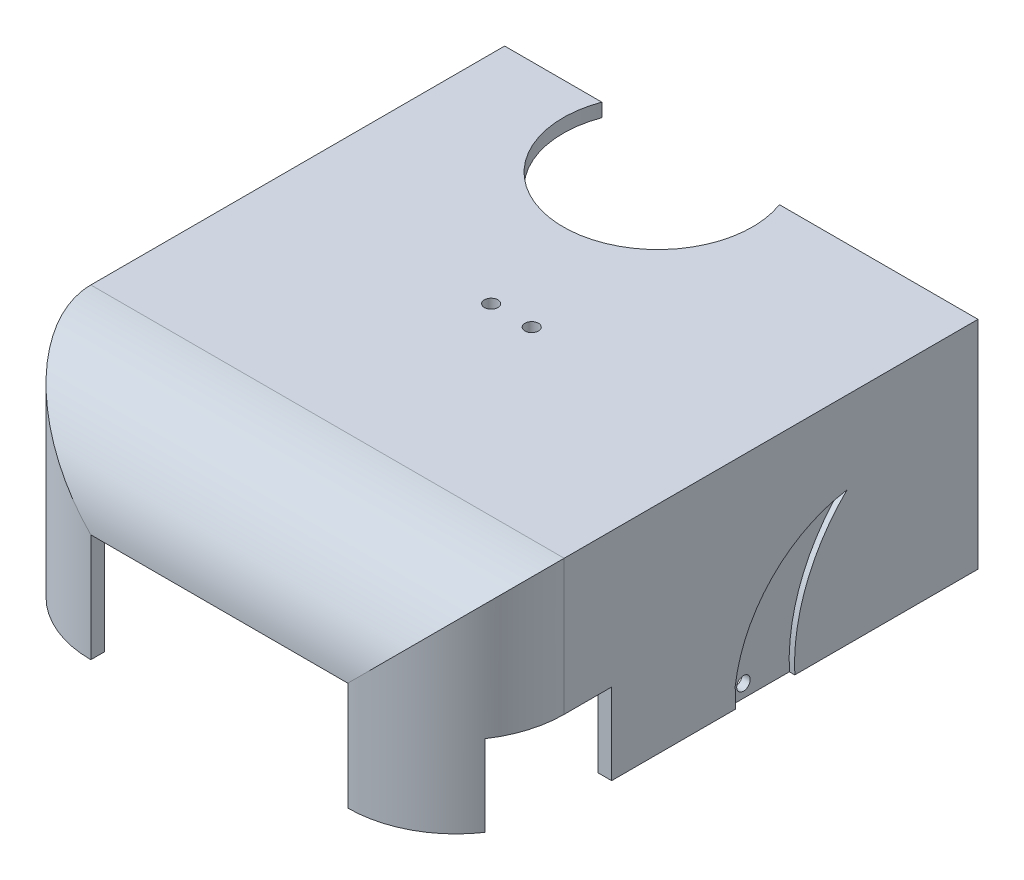
SolidWorks part; units mm, degrees
ref_plane "前基準面" through (0, 0, 0) normal (0, 0, 1) x (1, 0, 0)
ref_plane "上基準面" through (0, 0, 0) normal (0, 1, 0) x (1, 0, 0)
ref_plane "右基準面" through (0, 0, 0) normal (1, 0, 0) x (0, 0, -1)
sketch "草圖1" plane through (0, 0, 0) normal (0, 0, 1) x (1, 0, 0)
  line L1 (-87.5, -80) -> (87.5, -80)
  line L2 (-87.5, -80) -> (-87.5, 80)
  line L3 (-87.5, 80) -> (87.5, 80)
  line L4 (87.5, -80) -> (87.5, 80)
  line L5 (-87.5, -80) -> (87.5, 80) construction
  line L6 (-87.5, 80) -> (87.5, -80) construction
  point P0 (0, 0)
  dimension "D1" = 175
  dimension "D2" = 160
extrude "填料-伸長1" add sketch "草圖1" along normal blind 193
sketch "草圖4" plane through (0, 0, 0) normal (0, 1, 0) x (1, 0, 0)
  line L0 (0, 0) -> (0, -200)
  line L1 (0, -200) -> (-165, -200)
  line L2 (-165, -200) -> (-165, 0)
  line L3 (0, -200) -> (110, -200)
  line L4 (110, -200) -> (110, 0)
  line L5 (110, 0) -> (-165, 0)
  dimension "D1" = 165
  dimension "D2" = 200
sketch "草圖5" plane through (0, 0, 0) normal (1, 0, 0) x (0, 0, -1)
  line L0 (-200, 0) -> (-200, 160)
  line L1 (0, 0) -> (-200, 0) construction
  line L2 (-200, 160) -> (0, 160)
  dimension "D1" = 160
fillet "圓角8" radius 40 4 edges at (87.5, 0, 193) (0, 80, 193) (-87.5, 0, 193) (0, -80, 193)
shell "薄殼2" thickness 5
ref_plane "平面1" through (85, 0, 0) normal (1, 0, 0) x (0, 0, -1)
ref_plane "平面2" through (0, 80, 0) normal (0, 1, 0) x (1, 0, 0)
sketch "草圖8" plane through (0, 80, 0) normal (0, 1, 0) x (1, 0, 0)
  line L1 (87.5, 0) -> (-87.5, 0) construction
  line L3 (-87.5, 0) -> (17, 0)
  line L4 (-87.5, 0) -> (-87.5, -197.279)
  line L5 (-87.5, -197.279) -> (17, -197.279)
  line L6 (17, 0) -> (17, -197.279)
sketch "草圖9" plane through (0, 0, 193) normal (0, 0, 1) x (1, 0, 0)
  line L1 (-47.5, 40) -> (47.5, 40)
  line L2 (-47.5, 40) -> (-47.5, -40)
  line L3 (-47.5, -40) -> (47.5, -40)
  line L4 (47.5, 40) -> (47.5, -40)
extrude "除料-伸長3" cut sketch "草圖9" against normal blind 10
sketch "草圖10" plane through (0, 80, 0) normal (0, 1, 0) x (1, 0, 0)
  line L0 (0, 0) -> (-87.5, 0) construction
  line L1 (87.5, 0) -> (-87.5, 0) construction
  line L2 (-87.5, 0) -> (-43.75, 0) construction
  line L3 (-43.75, 0) -> (-87.5, 0) construction
  line L4 (-87.5, 0) -> (-65.625, 0) construction
  line L5 (-65.625, 0) -> (-43.75, -12.1031) construction
  line L6 (-43.75, 0) -> (-43.75, -31.8331) construction
  line L7 (-43.75, -12.1031) -> (-18.75, -12.1031)
  circle A0 centre (-18.75, -12.1031) radius 35
  dimension "D1" = 25
  dimension "D2" = 25
extrude "除料-伸長4" cut sketch "草圖10" against normal blind 160 contours A0
ref_plane "平面3" through (90, 0, 0) normal (1, 0, 0) x (0, 0, -1)
sketch "草圖12" plane through (90, 0, 0) normal (1, 0, 0) x (0, 0, -1)
  line L1 (-175.4577, -30) -> (-135.4577, 30) construction
  line L3 (-135.4577, -30) -> (-135.4577, 30)
  line L7 (-135.4577, 30) -> (-175.4577, 30)
  line L8 (-175.4577, 30) -> (-175.4577, -30)
  line L9 (-175.4577, -30) -> (-135.4577, -30)
  line L10 (0, 0) -> (-208.2911, 0) construction
  line L11 (-175.4577, 30) -> (-135.4577, -30) construction
  point P4 (-155.4577, 0)
  dimension "D1" = 60
  dimension "D2" = 40
extrude "除料-伸長5" cut sketch "草圖12" against normal blind 20
extrude "除料-伸長6" cut sketch "草圖4" against normal blind 80 contours L1 L2 L5 L4 L3
sketch "草圖15" plane through (0, 80, 0) normal (0, 1, 0) x (1, 0, 0)
  line L0 (0, -100) -> (0, -85)
  line L1 (0, -85) -> (0, -70)
  line L2 (15, -85) -> (0, -85)
  line L3 (0, -85) -> (-15, -85)
  line L4 (-87.5, 0) -> (17, 0) construction
  circle A0 centre (0, -85) radius 15 construction
  circle A1 centre (7.5, -85) radius 2.5
  circle A3 centre (-7.5, -85) radius 2.5
  dimension "D1" = 85
extrude "除料-伸長7" cut sketch "草圖15" against normal blind 5
sketch "草圖17" plane through (-87.5, 0, 0) normal (-1, 0, 0) x (0, 0, 1)
  line L0 (0, 0) -> (65, 0) construction
  line L1 (0, 0) -> (153, 0) construction
  line L6 (65, 0) -> (65, -10)
  line L7 (65, -10) -> (85, -10)
  line L8 (85, -10) -> (85, 20)
  line L9 (85, 20) -> (65, 20)
  line L10 (65, 20) -> (65, 0)
  line L11 (65, 20) -> (65, 30) construction
  line L12 (130, 35) -> (130, 40) construction
  line L13 (130, 40) -> (142.5, 40) construction
  line L14 (65, 30) -> (100, 30) construction
  line L15 (65, 25) -> (70, 25) construction
  line L16 (100, 30) -> (100, 0) construction
  line L17 (100, 25) -> (95, 25) construction
  circle A0 centre (130, 40) radius 2.5
  circle A1 centre (142.5, 40) radius 2.5
  circle A3 centre (70, 25) radius 2.5
  circle A4 centre (95, 25) radius 2.5
  dimension "D5" = 35
  dimension "D9" = 5
  dimension "D1" = 65
  dimension "D2" = 20
  dimension "D3" = 10
  dimension "D4" = 20
  dimension "D6" = 5
  dimension "D7" = 12.5
  dimension "D8" = 10
extrude "除料-伸長9" cut sketch "草圖17" against normal blind 5
sketch "草圖18" plane through (87.5, 0, 0) normal (1, 0, 0) x (0, 0, -1)
  line L0 (-67.7288, 0) -> (-89.7288, 0)
  line L1 (-135.4577, 0) -> (0, 0) construction
  line L6 (-89.7288, 0) -> (-89.6284, 2.2956)
  line L7 (-89.7693, 7.2936) -> (-89.6284, 2.2956)
  arc A2 (-89.7693, 7.2936) -> (-48.4374, 49.5892) centre (-40.9952, 0.9738) cw
  arc A3 (-48.4374, 49.5892) -> (-67.7288, 0) centre (-3.3955, 3.5198) ccw
  dimension "D1" = 22
  dimension "D2" = 5
extrude "除料-伸長10" cut sketch "草圖18" against normal blind 2 contours A3 L0 L6 L7 A2
ref_plane "平面4" through (87.5, 0, 0) normal (1, 0, 0) x (0, 0, -1)
sketch "草圖23" plane through (85.5, 0, 0) normal (1, 0, 0) x (0, 0, -1)
  line L0 (-89.6988, 4.7946) -> (-84.6988, 4.7946) construction
  line L1 (-89.7693, 7.2936) -> (-89.6284, 2.2956) construction
  circle A0 centre (-84.6988, 4.7946) radius 2.5
extrude "除料-伸長13" cut sketch "草圖23" against normal blind 5 contours A0
